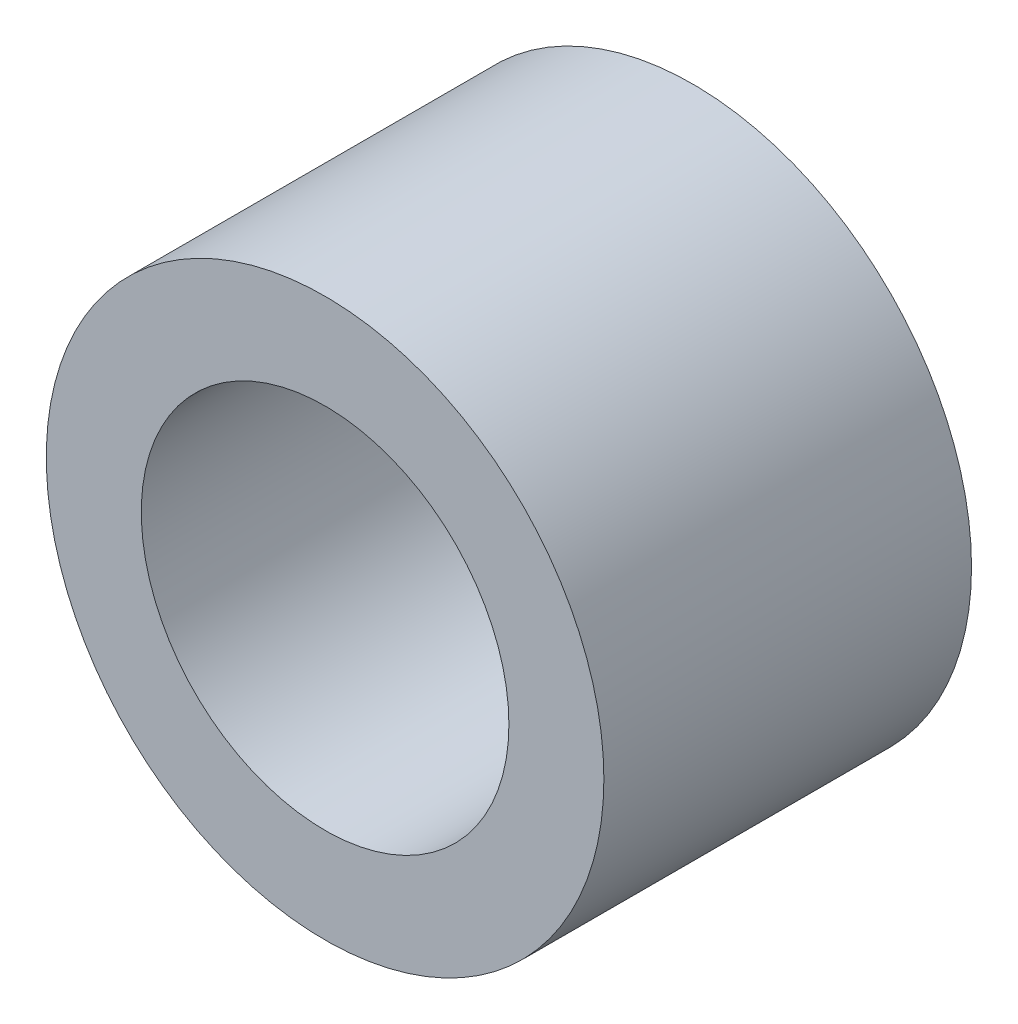
SolidWorks part; units mm, degrees
material "Brass"
ref_plane "Top Plane" through (0, 0, 0) normal (0, 0, 1) x (1, 0, 0)
ref_plane "Front Plane" through (0, 0, 0) normal (0, 1, 0) x (1, 0, 0)
ref_plane "Right Plane" through (0, 0, 0) normal (1, 0, 0) x (0, 0, -1)
sketch "Sketch1" plane through (0, 0, 0) normal (0, 0, 1) x (1, 0, 0)
  circle A0 centre (0, 0) radius 1.5
  circle A1 centre (0, 0) radius 2.275
  dimension "D1" = 3
  dimension "D2" = 4.55
extrude "Boss-Extrude1" add sketch "Sketch1" along normal blind 3
